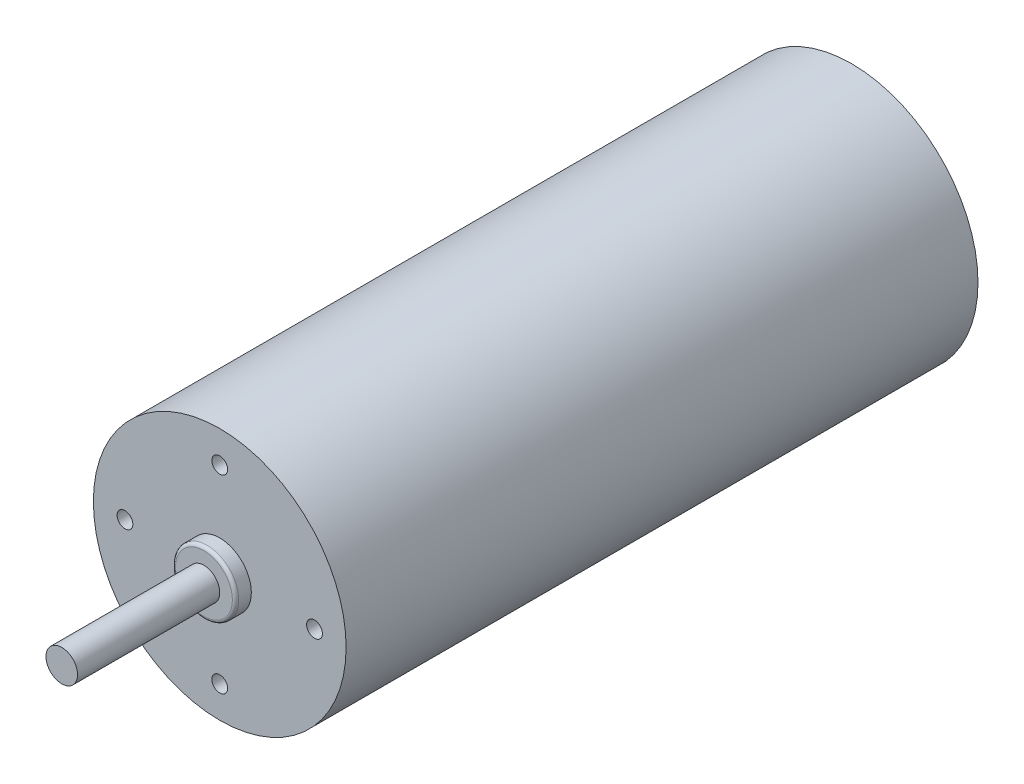
SolidWorks part; units mm, degrees
ref_plane "Front Plane" through (0, 0, 0) normal (0, 0, 1) x (1, 0, 0)
ref_plane "Top Plane" through (0, 0, 0) normal (0, 1, 0) x (1, 0, 0)
ref_plane "Right Plane" through (0, 0, 0) normal (1, 0, 0) x (0, 0, -1)
sketch "Sketch1" plane through (0, 0, 0) normal (0, 0, 1) x (1, 0, 0)
  circle A0 centre (0, 0) radius 4
  dimension "D1" = 8
extrude "Boss-Extrude1" add sketch "Sketch1" along normal blind 20
sketch "Sketch2" plane through (0, 0, 20) normal (0, 0, 1) x (1, 0, 0)
  circle A0 centre (0, 0) radius 1
  circle A1 centre (0, 0) radius 0.5
  dimension "D1" = 2
  dimension "D2" = 1
extrude "Boss-Extrude2" add sketch "Sketch2" along normal blind 0.5
sketch "Sketch4" plane through (0, 0, 20) normal (0, 0, 1) x (1, 0, 0)
  circle A0 centre (0, 0) radius 0.5
extrude "Boss-Extrude3" add sketch "Sketch4" along normal blind 5
fillet "Fillet2" radius 0.1 1 edges at (1, 0, 20.5)
sketch "Sketch5" plane through (0, 0, 20) normal (0, 0, 1) x (1, 0, 0)
  line L0 (0, 4) -> (0, -4) construction
  line L1 (4, 0) -> (-4, 0) construction
  circle A0 centre (0, 3) radius 0.25
  circle A1 centre (0, 0) radius 4 construction
  circle A2 centre (0, -3) radius 0.25
  circle A3 centre (3, 0) radius 0.25
  circle A4 centre (-3, 0) radius 0.25
  dimension "D1" = 0.5
  dimension "D2" = 0.5
  dimension "D3" = 1
  dimension "D4" = 1
extrude "Cut-Extrude1" cut sketch "Sketch5" against normal through all
